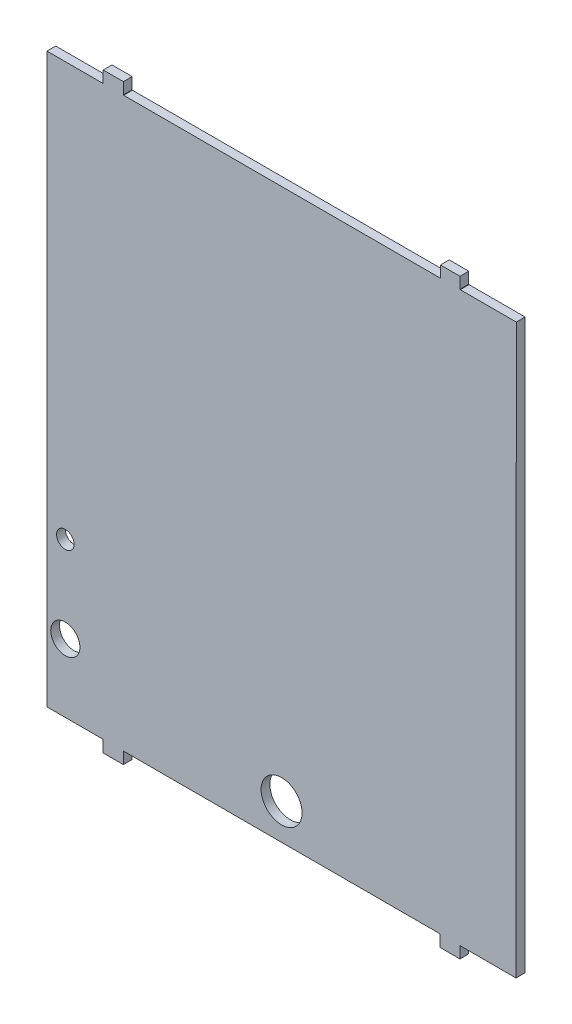
SolidWorks part; units mm, degrees
ref_plane "Front Plane" through (0, 0, 0) normal (0, 0, 1) x (1, 0, 0)
ref_plane "Top Plane" through (0, 0, 0) normal (0, 1, 0) x (1, 0, 0)
ref_plane "Right Plane" through (0, 0, 0) normal (1, 0, 0) x (0, 0, -1)
sketch "Model" plane through (0, 0, 0) normal (0, 0, 1) x (1, 0, 0)
  line L0 (683.6156, 410.2862) -> (683.133, 409.8036)
  line L1 (683.6156, 410.2862) -> (1233.5764, 410.2862)
  line L2 (1234.0844, 389.7376) -> (1234.0844, 409.8036)
  line L3 (648.0048, 409.702) -> (647.4968, 410.2862)
  line L4 (647.4968, 1399.2352) -> (648.0048, 1399.7432)
  line L5 (1234.0844, 389.7376) -> (1269.238, 389.7376)
  line L6 (683.133, 1399.8448) -> (683.641, 1399.3368)
  line L7 (683.133, 389.7376) -> (683.133, 409.8036)
  line L8 (1235.202, 1399.8448) -> (1234.7448, 1399.3368)
  line L9 (648.0048, 389.7376) -> (683.133, 389.7376)
  line L10 (1269.238, 1399.7432) -> (1269.7206, 1399.2352)
  line L11 (683.133, 1399.8448) -> (683.133, 1419.7076)
  line L12 (648.0048, 1399.7432) -> (648.0048, 1419.7076)
  line L13 (1233.5764, 410.2862) -> (1234.0844, 409.8036)
  line L14 (1235.202, 1399.8448) -> (1235.202, 1419.3012)
  line L15 (683.641, 1399.3368) -> (1234.7448, 1399.3368)
  line L17 (1269.238, 1399.7432) -> (1269.238, 1419.3012)
  line L18 (648.0048, 1419.7076) -> (683.133, 1419.7076)
  line L21 (1269.238, 409.8036) -> (1269.238, 409.9052)
  line L23 (1269.238, 409.9052) -> (1366.8248, 409.829)
  line L25 (550.0116, 410.2862) -> (647.4968, 410.2862)
  line L29 (1269.238, 389.7376) -> (1269.238, 409.8036)
  line L30 (648.0048, 389.7376) -> (648.0048, 409.702)
  line L32 (1235.202, 1419.3012) -> (1269.238, 1419.3012)
  line L50 (1269.7206, 1399.2352) -> (1367.3074, 1399.2352)
  line L53 (1366.8248, 409.829) -> (1367.3074, 1399.2352)
  line L62 (550.0116, 1399.2352) -> (647.4968, 1399.2352)
  line L64 (550.0116, 410.2862) -> (550.0116, 1399.2352)
  circle A66 centre (958.6214, 472.313) radius 35.6997
  circle A68 centre (582.0156, 528.8026) radius 25.4
  circle A70 centre (582.0156, 678.815) radius 15.24
  dimension "D1" = 71.3994
  dimension "D2" = 50.8
  dimension "D3" = 30.48
extrude "Boss-Extrude2" add sketch "Model" along normal blind 15.24
scale "Scale1" scale about centroid uniform scaling yes scale factor 0.1
